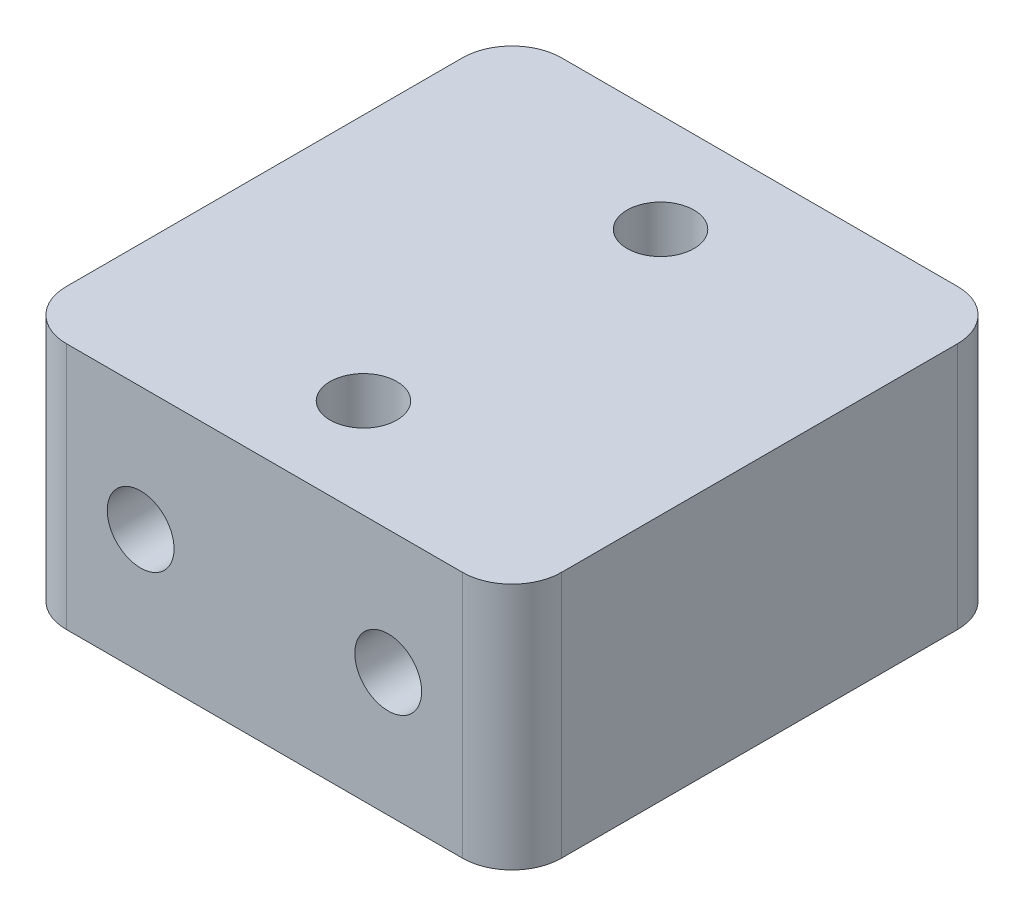
SolidWorks part; units mm, degrees
material "PLA"
ref_plane "前视基准面" through (0, 0, 0) normal (0, 0, 1) x (1, 0, 0)
ref_plane "上视基准面" through (0, 0, 0) normal (0, 1, 0) x (1, 0, 0)
ref_plane "右视基准面" through (0, 0, 0) normal (1, 0, 0) x (0, 0, -1)
sketch "草图1" plane through (0, 0, 0) normal (0, 1, 0) x (1, 0, 0)
  line L1 (-10, -10) -> (10, -10)
  line L2 (-10, -10) -> (-10, 10)
  line L3 (-10, 10) -> (10, 10)
  line L4 (10, -10) -> (10, 10)
  line L5 (0, 10) -> (0, -10) construction
  line L6 (-10, 0) -> (10, 0) construction
  circle A4 centre (0, 6) radius 1.35
  circle A5 centre (0, -6) radius 1.35
  dimension "D1" = 2.7
  dimension "D2" = 12
  dimension "D4" = 20
  dimension "D5" = 20
extrude "凸台-拉伸1" add sketch "草图1" along normal blind 10
sketch "草图2" plane through (10, 0, 0) normal (1, 0, 0) x (0, 0, -1)
  line L0 (10, 0) -> (-10, 0) construction
  line L2 (10, 0) -> (10, 10)
  line L3 (10, 10) -> (-10, 10)
  line L4 (-10, 0) -> (-10, 10)
  line L6 (10, 0) -> (10, -20)
  line L7 (10, -20) -> (-10, -20)
  line L8 (-10, 0) -> (-10, -20)
  line L9 (0, 0) -> (0, -20) construction
  line L10 (7, -10) -> (10, -10) construction
  circle A0 centre (7, -10) radius 1.6
  circle A2 centre (-7, -10) radius 1.6
  dimension "D3" = 3.2
  dimension "D1" = 10
  dimension "D2" = 14
extrude "凸台-拉伸2" [suppressed] add sketch "草图2" along normal blind 6
sketch "草图3" plane through (0, 0, -10) normal (0, 0, -1) x (-1, 0, 0)
  line L0 (0, 0) -> (0, 10) construction
  line L1 (-10, 10) -> (10, 10) construction
  line L2 (5, 5) -> (0, 5) construction
  circle A1 centre (5, 5) radius 1.35
  circle A2 centre (-5, 5) radius 1.35
  dimension "D1" = 10
  dimension "D2" = 2.7
extrude "切除-拉伸1" cut sketch "草图3" against normal through all
fillet "圆角1" radius 2 4 edges at (10, 5, 10) (-10, 5, 10) (10, 5, -10) (-10, 5, -10)
